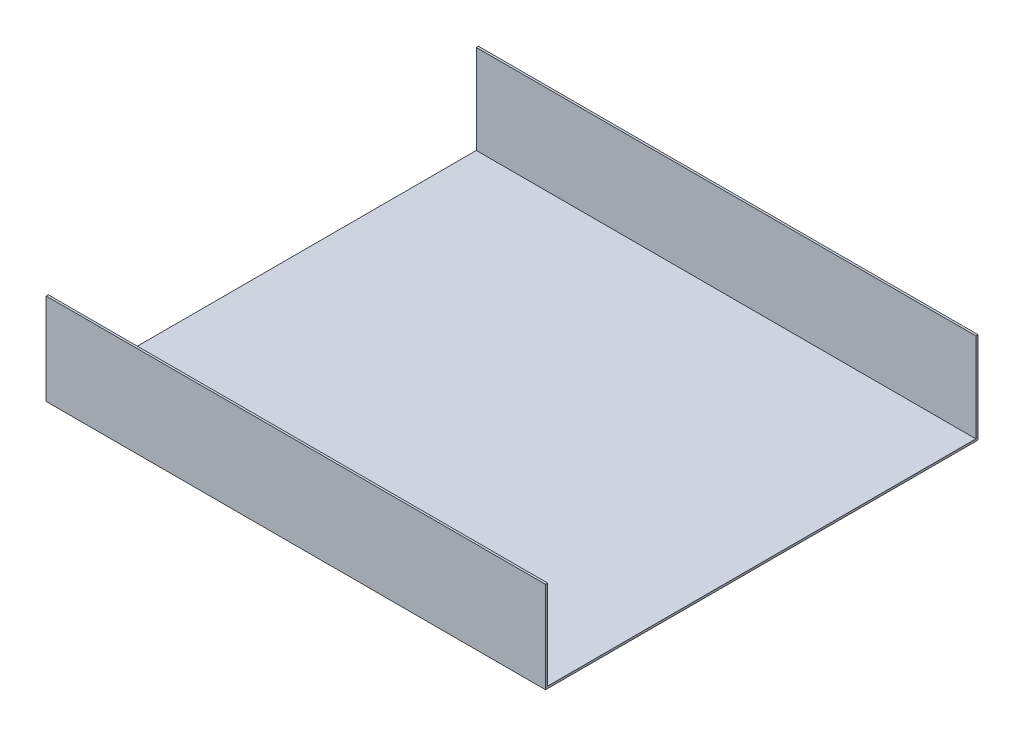
SolidWorks part; units mm, degrees
material "AISI 304"
ref_plane "Alzado" through (0, 0, 0) normal (0, 0, 1) x (1, 0, 0)
ref_plane "Planta" through (0, 0, 0) normal (0, 1, 0) x (1, 0, 0)
ref_plane "Vista lateral" through (0, 0, 0) normal (1, 0, 0) x (0, 0, -1)
sketch "Croquis1" plane through (0, 0, 0) normal (1, 0, 0) x (0, 0, -1)
  line L0 (0, 25) -> (0, 0)
  line L1 (0, 0) -> (120, 0)
  line L2 (120, 0) -> (120, 25)
  line L3 (0, 25) -> (120, 25)
  dimension "D1" = 120
  dimension "D2" = 25
extrude "Saliente-Extruir1" add sketch "Croquis1" along normal blind 140
shell "Vaciado1" thickness 0.6
